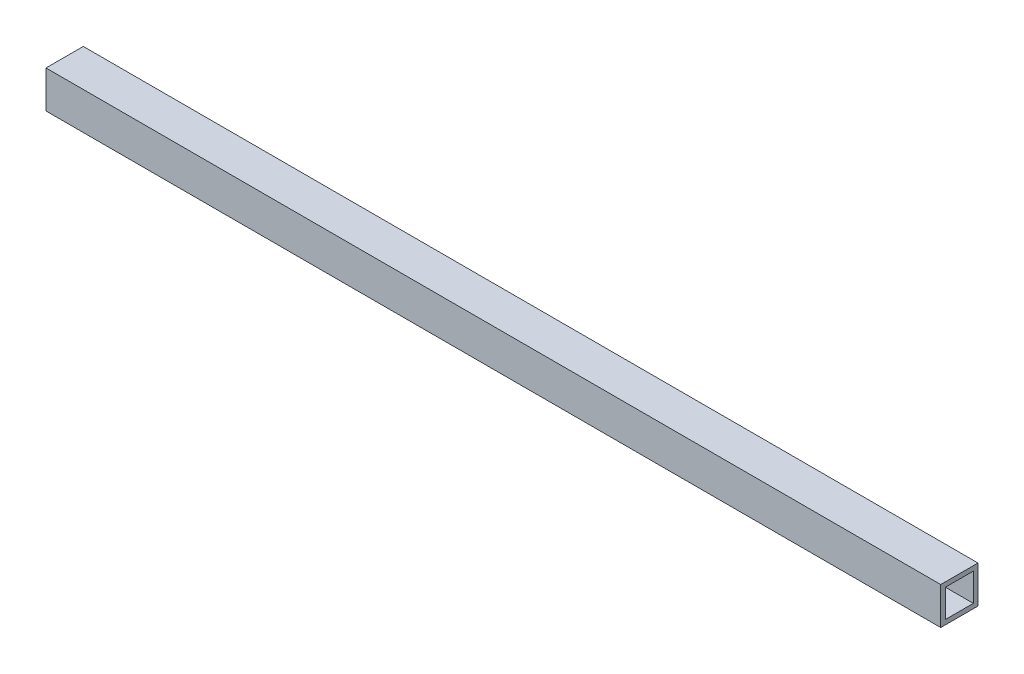
SolidWorks part; units mm, degrees
ref_plane "Front Plane" through (0, 0, 0) normal (0, 0, 1) x (1, 0, 0)
ref_plane "Top Plane" through (0, 0, 0) normal (0, 1, 0) x (1, 0, 0)
ref_plane "Right Plane" through (0, 0, 0) normal (1, 0, 0) x (0, 0, -1)
sketch "Sketch2" plane through (0, 0, 0) normal (1, 0, 0) x (0, 0, -1)
  line L1 (-12.7, 12.7) -> (12.7, 12.7)
  line L2 (-12.7, 12.7) -> (-12.7, -12.7)
  line L3 (-12.7, -12.7) -> (12.7, -12.7)
  line L4 (12.7, 12.7) -> (12.7, -12.7)
  line L5 (-12.7, 12.7) -> (12.7, -12.7) construction
  line L6 (-12.7, -12.7) -> (12.7, 12.7) construction
  line L7 (-9.525, -9.525) -> (9.525, -9.525)
  line L8 (-9.525, -9.525) -> (-9.525, 9.525)
  line L9 (-9.525, 9.525) -> (9.525, 9.525)
  line L10 (9.525, -9.525) -> (9.525, 9.525)
  line L11 (-9.525, -9.525) -> (9.525, 9.525) construction
  line L12 (-9.525, 9.525) -> (9.525, -9.525) construction
  point P0 (0, 0)
  point P6 (0, 0)
  dimension "D1" = 25.4
  dimension "D2" = 25.4
  dimension "D3" = 19.05
extrude "Boss-Extrude1" add sketch "Sketch2" along normal blind 609.6
